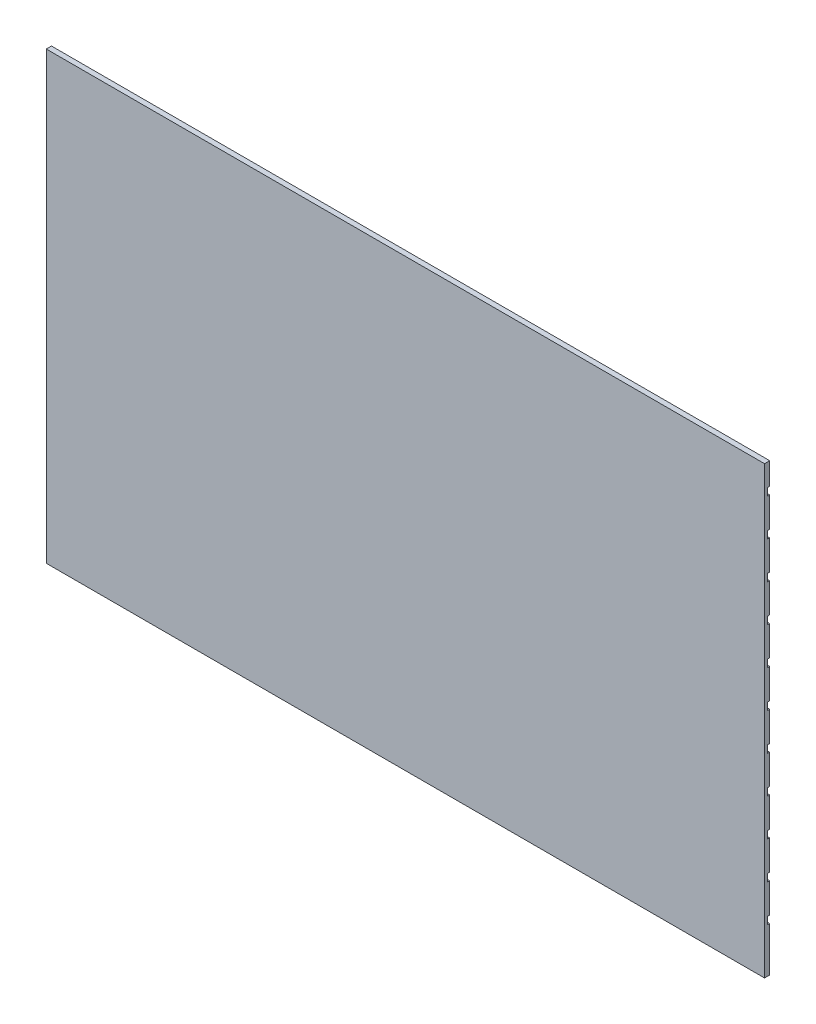
SolidWorks part; units mm, degrees
ref_plane "Front Plane" through (0, 0, 0) normal (0, 0, 1) x (1, 0, 0)
ref_plane "Top Plane" through (0, 0, 0) normal (0, 1, 0) x (1, 0, 0)
ref_plane "Right Plane" through (0, 0, 0) normal (1, 0, 0) x (0, 0, -1)
sketch "Sketch2" plane through (0, 0, 0) normal (1, 0, 0) x (0, 0, -1)
  line L1 (0, 0) -> (17.78, 0)
  line L2 (0, 0) -> (0, -1524)
  line L3 (0, -1524) -> (17.78, -1524)
  line L4 (17.78, 0) -> (17.78, -1524)
  dimension "D1" = 17.78
  dimension "D2" = 1524
extrude "Boss-Extrude1" add sketch "Sketch2" along normal blind 2457.45
sketch "Sketch3" plane through (0, 0, -17.78) normal (0, 0, -1) x (-1, 0, 0)
  line L0 (-2457.45, -1524) -> (-2457.45, 0) construction
  line L1 (-2457.45, -76.2) -> (0, -76.2)
  line L2 (-2457.45, -76.2) -> (-2457.45, -101.6)
  line L3 (-2457.45, -101.6) -> (0, -101.6)
  line L4 (0, -76.2) -> (0, -101.6)
  line L5 (0, -1524) -> (0, 0) construction
  line L6 (-2457.45, 0) -> (0, 0) construction
  line L7 (-2457.45, -228.6) -> (0, -228.6)
  line L8 (-2457.45, -203.2) -> (0, -203.2)
  line L9 (-2457.45, -203.2) -> (-2457.45, -228.6)
  line L10 (0, -203.2) -> (0, -228.6)
  line L11 (-2457.45, -355.6) -> (0, -355.6)
  line L12 (-2457.45, -330.2) -> (0, -330.2)
  line L13 (-2457.45, -330.2) -> (-2457.45, -355.6)
  line L14 (0, -330.2) -> (0, -355.6)
  line L15 (-2457.45, -482.6) -> (0, -482.6)
  line L16 (-2457.45, -457.2) -> (0, -457.2)
  line L17 (-2457.45, -457.2) -> (-2457.45, -482.6)
  line L18 (0, -457.2) -> (0, -482.6)
  line L19 (-2457.45, -609.6) -> (0, -609.6)
  line L20 (-2457.45, -584.2) -> (0, -584.2)
  line L21 (-2457.45, -584.2) -> (-2457.45, -609.6)
  line L22 (0, -584.2) -> (0, -609.6)
  line L23 (-2457.45, -736.6) -> (0, -736.6)
  line L24 (-2457.45, -711.2) -> (0, -711.2)
  line L25 (-2457.45, -711.2) -> (-2457.45, -736.6)
  line L26 (0, -711.2) -> (0, -736.6)
  line L27 (-2457.45, -863.6) -> (0, -863.6)
  line L28 (-2457.45, -838.2) -> (0, -838.2)
  line L29 (-2457.45, -838.2) -> (-2457.45, -863.6)
  line L30 (0, -838.2) -> (0, -863.6)
  line L31 (-2457.45, -990.6) -> (0, -990.6)
  line L32 (-2457.45, -965.2) -> (0, -965.2)
  line L33 (-2457.45, -965.2) -> (-2457.45, -990.6)
  line L34 (0, -965.2) -> (0, -990.6)
  line L35 (-2457.45, -1117.6) -> (0, -1117.6)
  line L36 (-2457.45, -1092.2) -> (0, -1092.2)
  line L37 (-2457.45, -1092.2) -> (-2457.45, -1117.6)
  line L38 (0, -1092.2) -> (0, -1117.6)
  line L39 (-2457.45, -1244.6) -> (0, -1244.6)
  line L40 (-2457.45, -1219.2) -> (0, -1219.2)
  line L41 (-2457.45, -1219.2) -> (-2457.45, -1244.6)
  line L42 (0, -1219.2) -> (0, -1244.6)
  line L43 (-2457.45, -1371.6) -> (0, -1371.6)
  line L44 (-2457.45, -1346.2) -> (0, -1346.2)
  line L45 (-2457.45, -1346.2) -> (-2457.45, -1371.6)
  line L46 (0, -1346.2) -> (0, -1371.6)
  dimension "D1" = 25.4
  dimension "D2" = 76.2
  dimension "D3" = 11
extrude "Cut-Extrude1" cut sketch "Sketch3" against normal blind 7.62
